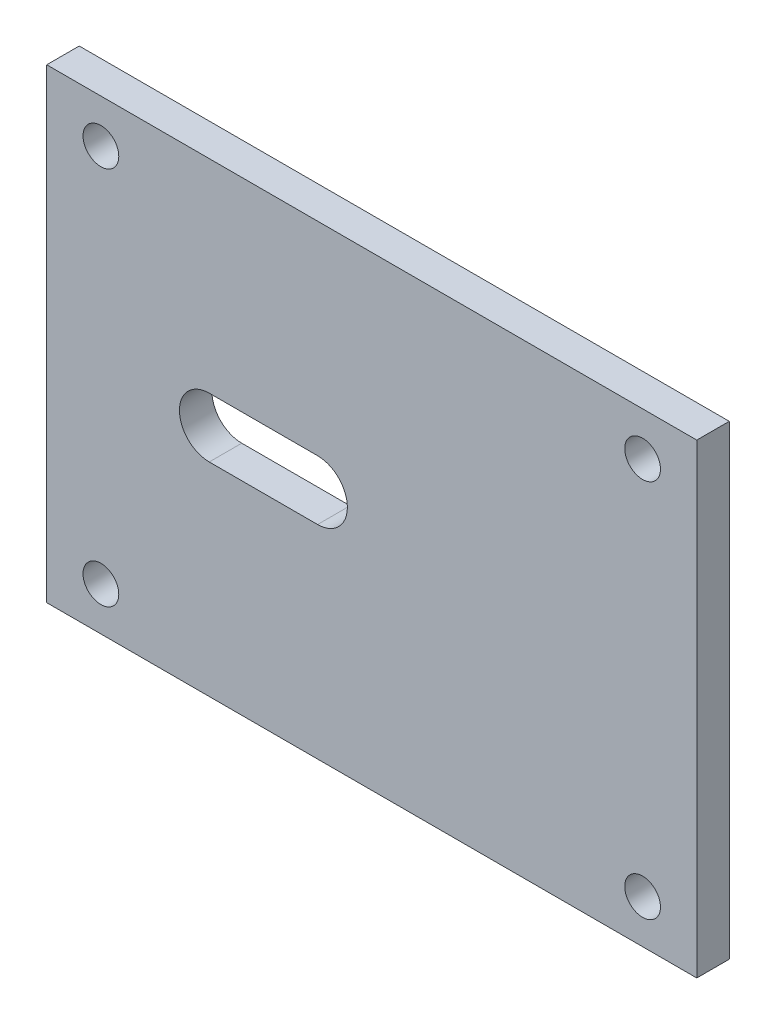
SolidWorks part; units mm, degrees
ref_plane "Plan de face" through (0, 0, 0) normal (0, 0, 1) x (1, 0, 0)
ref_plane "Plan de dessus" through (0, 0, 0) normal (0, 1, 0) x (1, 0, 0)
ref_plane "Plan de droite" through (0, 0, 0) normal (1, 0, 0) x (0, 0, -1)
sketch "Sketch1" plane through (0, 0, 0) normal (0, 0, 1) x (1, 0, 0)
  line L1 (25, -17.5) -> (-25, -17.5) construction
  line L2 (25, -17.5) -> (25, 17.5) construction
  line L3 (25, 17.5) -> (-25, 17.5) construction
  line L4 (-25, -17.5) -> (-25, 17.5) construction
  line L5 (25, -17.5) -> (-25, 17.5) construction
  line L6 (25, 17.5) -> (-25, -17.5) construction
  line L7 (30, -21.5) -> (-30, -21.5)
  line L8 (30, -21.5) -> (30, 21.5)
  line L9 (30, 21.5) -> (-30, 21.5)
  line L10 (-30, -21.5) -> (-30, 21.5)
  line L11 (30, -21.5) -> (-30, 21.5) construction
  line L12 (30, 21.5) -> (-30, -21.5) construction
  circle A0 centre (-25, 17.5) radius 1.65
  circle A1 centre (25, 17.5) radius 1.65
  circle A2 centre (25, -17.5) radius 1.65
  circle A3 centre (-25, -17.5) radius 1.65
  point P0 (0, 0)
  point P10 (0, 0)
  dimension "D3" = 3.3
  dimension "D1" = 35
  dimension "D2" = 50
  dimension "D4" = 43
  dimension "D5" = 60
extrude "Boss-Extrude1" add sketch "Sketch1" along normal blind 3
sketch "Sketch2" plane through (0, 0, 0) normal (0, 0, -1) x (-1, 0, 0)
  line L0 (15, 0) -> (5, 0) construction
  line L1 (15, -2.75) -> (5, -2.75)
  line L2 (15, 2.75) -> (5, 2.75)
  line L3 (30, 21.5) -> (30, -21.5) construction
  arc A0 (15, -2.75) -> (15, 2.75) centre (15, 0) ccw
  arc A1 (5, 2.75) -> (5, -2.75) centre (5, 0) ccw
  point P2 (10, 0)
  point P8 (7.5107, 0)
  dimension "D2" = 2.75
  dimension "D1" = 10
  dimension "D3" = 20
extrude "Cut-Extrude1" cut sketch "Sketch2" against normal through all
